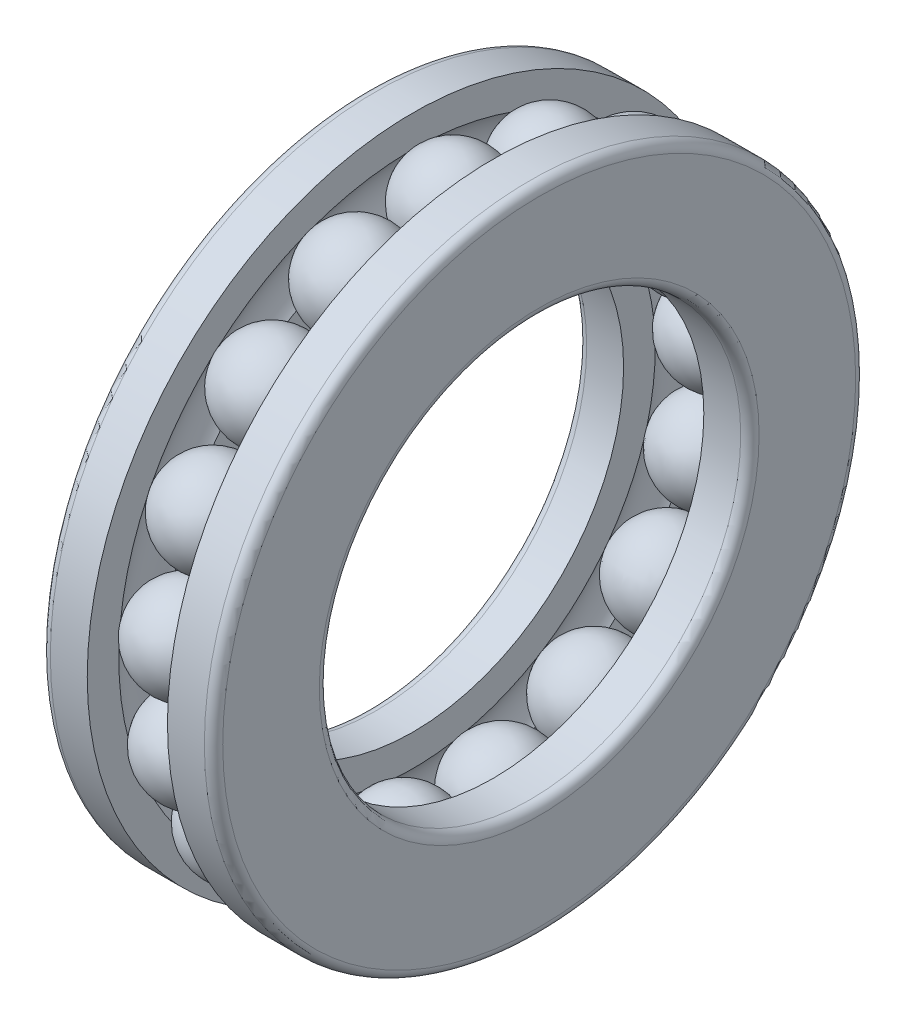
SolidWorks part; units mm, degrees
ref_plane "Plane1" through (0, 0, 0) normal (0, 0, 1) x (1, 0, 0)
ref_plane "Plane2" through (0, 0, 0) normal (0, 1, 0) x (1, 0, 0)
ref_plane "Plane3" through (0, 0, 0) normal (1, 0, 0) x (0, 0, -1)
sketch "Clipboard" plane through (0, 0, 0) normal (0, 0, 1) x (1, 0, 0)
  line L0 (-10, 0) -> (10, 0) construction
  line L1 (0, 0) -> (21.3836, -6.5376)
  line L2 (0, 0) -> (27.3662, 35.0271)
  line L3 (0, 0) -> (13.7666, -17.6205)
  line L4 (0, 0) -> (-22.3471, -0.7804)
  dimension "Count" = 52
  dimension "Show_count" = 52
  dimension "Max_count" = 17
sketch "InnRacSke" plane through (0, 0, 0) normal (0, 0, 1) x (1, 0, 0)
  line L0 (-6.6469, 40.1573) -> (-6.6469, 34.925)
  line L1 (-6.6469, 34.925) -> (-12.7635, 34.925)
  line L2 (-14.2875, 36.449) -> (-14.2875, 52.451)
  line L3 (-12.7635, 53.975) -> (-6.6469, 53.975)
  line L4 (-6.6469, 53.975) -> (-6.6469, 48.7427)
  line L5 (-34.925, 0) -> (34.925, 0) construction
  line L6 (0, 0) -> (0, 25.4) construction
  arc A0 (-12.7635, 34.925) -> (-14.2875, 36.449) centre (-12.7635, 36.449) cw
  arc A1 (-14.2875, 52.451) -> (-12.7635, 53.975) centre (-12.7635, 52.451) cw
  arc A2 (-6.6469, 48.7427) -> (-6.6469, 40.1573) centre (0, 44.45) ccw
revolve "Race" add sketch "InnRacSke" angle 360 about L5
ref_axis "Axis1" through (-50, 0, 0) along (1, 0, 0)
sketch "BalDetSke" plane through (0, 0, 0) normal (0, 0, 1) x (1, 0, 0)
  line L0 (-7.9375, 44.45) -> (7.9375, 44.45)
  line L1 (-14.5732, 44.45) -> (14.5732, 44.45) construction
  arc A0 (7.9375, 44.45) -> (-7.9375, 44.45) centre (0, 44.45) cw
revolve "BallDetailed" add sketch "BalDetSke" angle 360 about L1
sketch "BalSimSke" plane through (0, 0, 0) normal (0, 0, 1) x (1, 0, 0)
  line L0 (-25.4, 0) -> (25.4, 0) construction
  circle A0 centre (0, 44.45) radius 7.9375
revolve "BallsSimplified" [suppressed] add sketch "BalSimSke" angle 360 about L0
mirror "Mirror1" about plane through (0, 0, 0) normal (1, 0, 0) of "Race"
pattern_circular "BallsDetailed" count 17 every 21.176 about axis through (-50, 0, 0) along (1, 0, 0) of "BallDetailed"
sketch "CagSpiSke" plane through (0, 0, 0) normal (0, 0, 1) x (1, 0, 0)
  line L0 (1.9844, 35.7188) -> (1.9844, 53.1812)
  line L1 (1.9844, 53.1812) -> (-1.9844, 53.1812)
  line L2 (-1.9844, 53.1812) -> (-1.9844, 35.7188)
  line L3 (-1.9844, 35.7188) -> (1.9844, 35.7188)
  line L4 (-34.925, 0) -> (34.925, 0) construction
  line L5 (0, 0) -> (0, 50.8) construction
revolve "CageSpine" [suppressed] add sketch "CagSpiSke" angle 360 about L4
equation "\"BallCLRad@Clipboard\" =  ( \"OD@InnRacSke\" + \"ID@InnRacSke\" )  / 4"
equation "\"BallCLRad@BalSimSke\" = \"BallCLRad@Clipboard\""
equation "\"BallCLRad@BalDetSke\" = \"BallCLRad@Clipboard\""
equation "\"BallCLRad@InnRacSke\" = \"BallCLRad@Clipboard\""
equation "\"Ball_diameter@InnRacSke\" = \"Ball_diameter@BalDetSke\" - 0.05"
equation "\"Ball_diameter@BalSimSke\" = \"Ball_diameter@BalDetSke\""
equation "\"Max_count@Clipboard\" = int( 3.14159265 / atn(( \"Ball_diameter@BalDetSke\" / 2) / sqr( \"BallCLRad@Clipboard\"  *  \"BallCLRad@Clipboard\" - ( \"Ball_diameter@BalDetSke\" / 2) *  ( \"Ball_diameter@BalDetSke\" / 2))))"
equation "\"Max_count@Clipboard\" = ((sgn( \"Max_count@Clipboard\" - \"Count@Clipboard\" )-1)*( \"Max_count@Clipboard\" - \"Count@Clipboard\" ))/-2+ \"Count@Clipboard\""
equation "\"Count@BallsDetailed\" = int( \"Show_count@Clipboard\" ) "
equation "\"Count@BallsDetailed\" = ((sgn( \"Count@BallsDetailed\" - \"Max_count@Clipboard\" )-1)*( \"Count@BallsDetailed\" - \"Max_count@Clipboard\" ))/-2+ \"Max_count@Clipboard\""
equation "\"Count@BallsDetailed\" = ((sgn( \"Count@BallsDetailed\" - \"Min_count@Clipboard\" )+1)*( \"Count@BallsDetailed\" - \"Min_count@Clipboard\"))/2 +\"Min_count@Clipboard\""
equation "\"Angle@BallsDetailed\" = 360.0 / \"Max_count@Clipboard\""
equation "\"Angle@CageSpine\" =  \"Angle@BallsDetailed\" * ( \"Count@BallsDetailed\" -1 + int( \"Count@BallsDetailed\" / \"Max_count@Clipboard\" ) )  + 0.001 -  int( \"Count@BallsDetailed\" / \"Max_count@Clipboard\" ) * 0.001"
equation "\"Angle@CageSpine\" =  \"Angle@CageSpine\" * int( \"Min_count@Clipboard\" / 2) + int(1 / \"Min_count@Clipboard\")  * 0.001"
equation "\"Thickness@CagSpiSke\" =  \"Ball_diameter@BalDetSke\" * 0.25"
equation "\"OD@CagSpiSke\" = ( \"OD@InnRacSke\" + ( \"BallCLRad@Clipboard\" * 2 + \"Ball_diameter@BalDetSke\" )) / 2"
equation "\"ID@CagSpiSke\" = ( \"ID@InnRacSke\" + ( \"BallCLRad@Clipboard\" * 2 - \"Ball_diameter@BalDetSke\" )) / 2"
